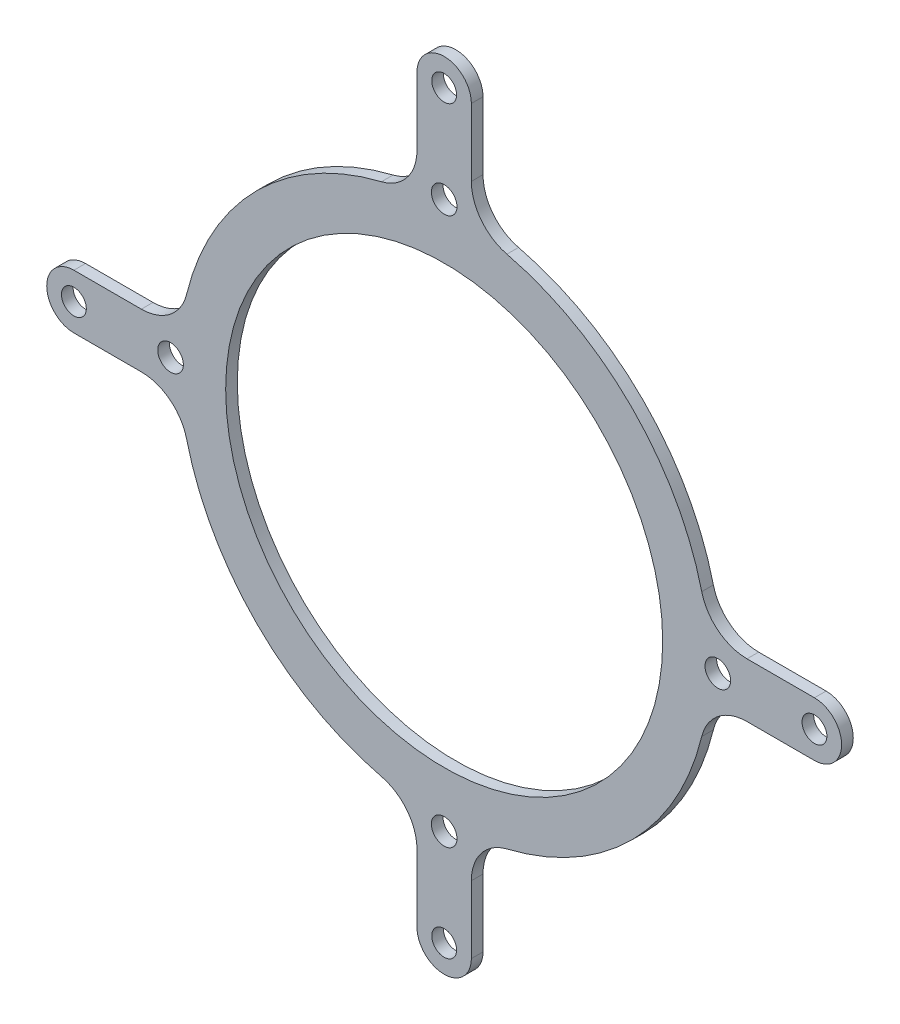
SolidWorks part; units mm, degrees
material "Thornel Mat VMA"
ref_plane "前视基准面" through (0, 0, 0) normal (0, 0, 1) x (1, 0, 0)
ref_plane "上视基准面" through (0, 0, 0) normal (0, 1, 0) x (1, 0, 0)
ref_plane "右视基准面" through (0, 0, 0) normal (1, 0, 0) x (0, 0, -1)
sketch "草图1" plane through (0, 0, 0) normal (0, 0, 1) x (1, 0, 0)
  line L0 (0, 0) -> (0, 47.7) construction
  line L1 (0, 47.7) -> (0, 34.15) construction
  line L2 (3.5, 47.7) -> (3.5, 34.15)
  line L3 (-3.5, 47.7) -> (-3.5, 34.15)
  line L4 (47.7, 0) -> (34.15, 0) construction
  line L5 (47.7, -3.5) -> (34.15, -3.5)
  line L6 (47.7, 3.5) -> (34.15, 3.5)
  line L7 (0, -47.7) -> (0, -34.15) construction
  line L8 (-3.5, -47.7) -> (-3.5, -34.15)
  line L9 (3.5, -47.7) -> (3.5, -34.15)
  line L10 (-47.7, 0) -> (-34.15, 0) construction
  line L11 (-47.7, 3.5) -> (-34.15, 3.5)
  line L12 (-47.7, -3.5) -> (-34.15, -3.5)
  circle A0 centre (0, 0) radius 28.15
  circle A1 centre (0, 0) radius 34.15
  arc A2 (3.5, 47.7) -> (-3.5, 47.7) centre (0, 47.7) ccw
  arc A3 (-3.5, 34.15) -> (3.5, 34.15) centre (0, 34.15) ccw
  circle A4 centre (0, 47.7) radius 1.6
  circle A5 centre (47.7, 0) radius 1.6
  arc A6 (47.7, -3.5) -> (47.7, 3.5) centre (47.7, 0) ccw
  arc A7 (34.15, 3.5) -> (34.15, -3.5) centre (34.15, 0) ccw
  circle A8 centre (0, -47.7) radius 1.6
  arc A9 (-3.5, -47.7) -> (3.5, -47.7) centre (0, -47.7) ccw
  arc A10 (3.5, -34.15) -> (-3.5, -34.15) centre (0, -34.15) ccw
  circle A11 centre (-47.7, 0) radius 1.6
  arc A12 (-47.7, 3.5) -> (-47.7, -3.5) centre (-47.7, 0) ccw
  arc A13 (-34.15, -3.5) -> (-34.15, 3.5) centre (-34.15, 0) ccw
  point P6 (0, 40.925)
  point P18 (40.925, 0)
  point P27 (0, -40.925)
  point P36 (-40.925, 0)
  point P43 (0, 0)
  dimension "D1" = 56.3
  dimension "D2" = 6
  dimension "D4" = 3.2
  dimension "D3" = 47.7
  dimension "D5" = 7
  dimension "D6" = 4
extrude "凸台-拉伸1" add sketch "草图1" along normal blind 1.5 contours A13 A1 A10 A7 A3 A0 | A1 A3 | L3 A3 A1 L2 A2 A4 | A1 A7 | L6 A7 A1 L5 A6 A5 | A1 A13 | A1 A13 L11 A12 L12 A11 | A1 A10 | L9 A10 A1 L8 A9 A8
fillet "圆角1" radius 6 8 edges at (-3.4954, 33.9706, 0.75) (3.4954, 33.9706, 0.75) (33.9706, 3.4954, 0.75) (33.9706, -3.4954, 0.75) (3.4954, -33.9706, 0.75) (-3.4954, -33.9706, 0.75) (-33.9706, -3.4954, 0.75) (-33.9706, 3.4954, 0.75)
sketch "草图3" plane through (0, 0, 1.5) normal (0, 0, 1) x (1, 0, 0)
  line L0 (0, 0) -> (-35.25, 0) construction
  circle A0 centre (0, 0) radius 35.25 construction
  circle A1 centre (-35.25, 0) radius 1.65
  circle A2 centre (0, 35.25) radius 1.65
  circle A3 centre (35.25, 0) radius 1.65
  circle A4 centre (0, -35.25) radius 1.65
  point P13 (0, 0)
  dimension "D1" = 70.5
  dimension "D3" = 3.3
  dimension "D2" = 4
extrude "切除-拉伸1" cut sketch "草图3" against normal blind 3
